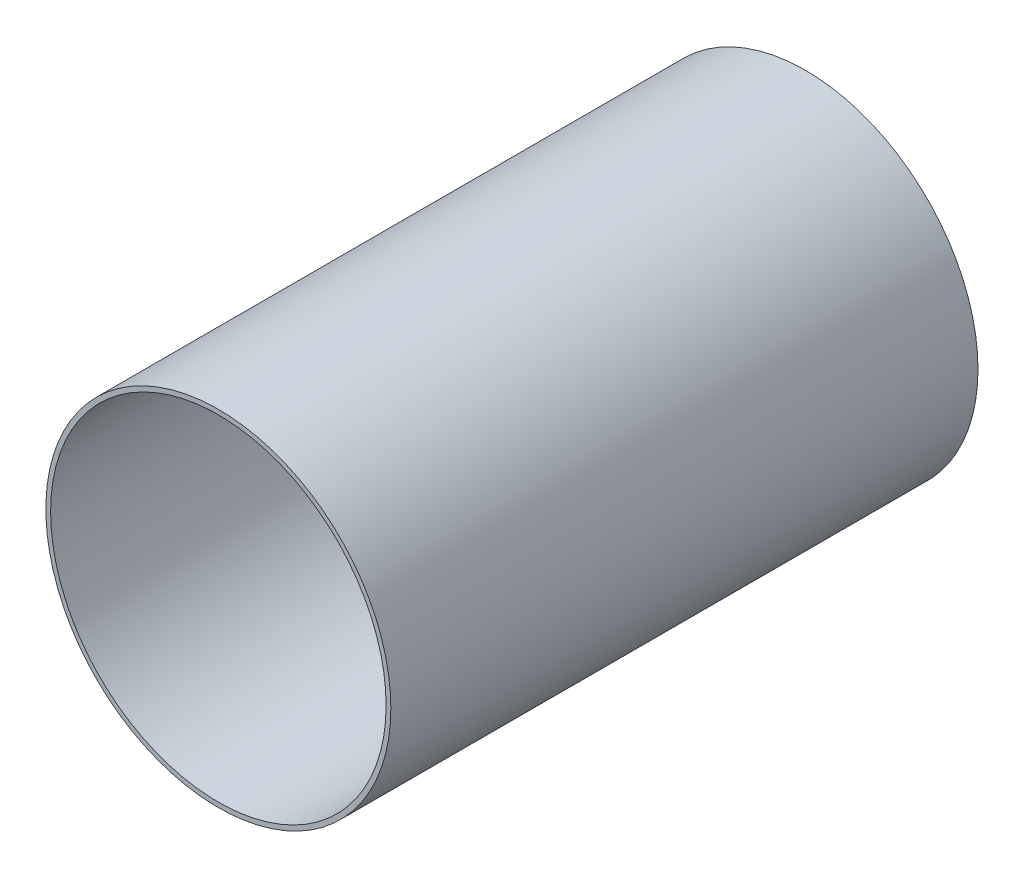
SolidWorks part; units mm, degrees
ref_plane "Plan de face" through (0, 0, 0) normal (0, 0, 1) x (1, 0, 0)
ref_plane "Plan de dessus" through (0, 0, 0) normal (0, 1, 0) x (1, 0, 0)
ref_plane "Plan de droite" through (0, 0, 0) normal (1, 0, 0) x (0, 0, -1)
sketch "Esquisse2" plane through (0, 0, 0) normal (0, 0, 1) x (1, 0, 0)
  circle A0 centre (0, 0) radius 78.359
  circle A1 centre (0, 0) radius 76.2
  dimension "D1" = 156.718
  dimension "D2" = 152.4
extrude "Boss.-Extru.1" add sketch "Esquisse2" along normal blind 266.7
